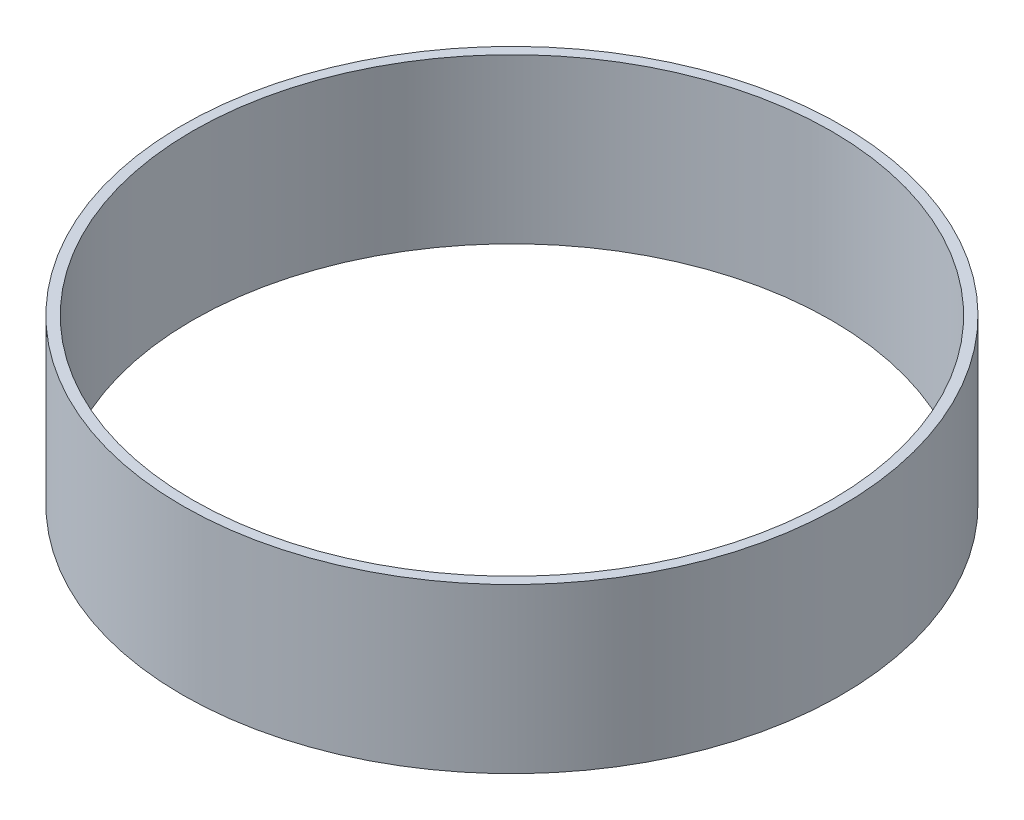
SolidWorks part; units mm, degrees
ref_plane "Front Plane" through (0, 0, 0) normal (0, 0, 1) x (1, 0, 0)
ref_plane "Top Plane" through (0, 0, 0) normal (0, 1, 0) x (1, 0, 0)
ref_plane "Right Plane" through (0, 0, 0) normal (1, 0, 0) x (0, 0, -1)
sketch "Sketch1" plane through (0, 0, 0) normal (0, 1, 0) x (1, 0, 0)
  circle A0 centre (0, 0) radius 51.1048
  circle A1 centre (0, 0) radius 49.53
  dimension "D1" = 99.06
  dimension "D2" = 102.2096
extrude "Boss-Extrude1" add sketch "Sketch1" along normal blind 25.4
